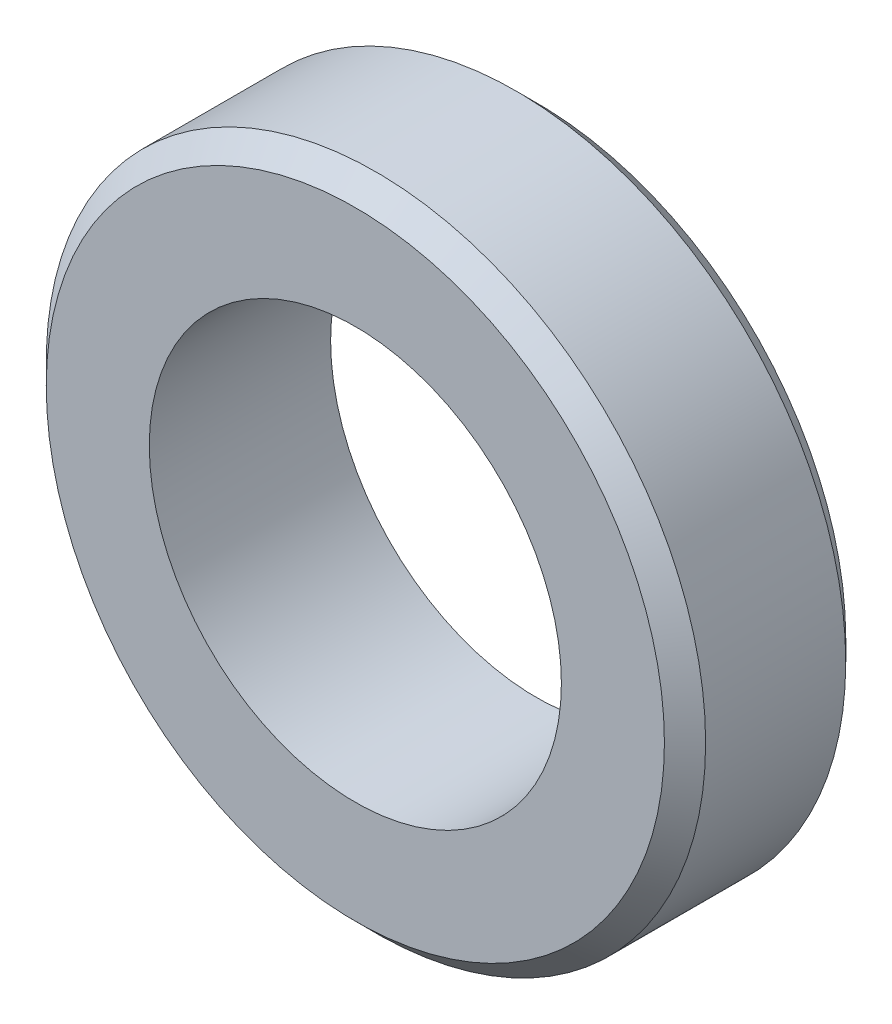
SolidWorks part; units mm, degrees
ref_plane "Front Plane" through (0, 0, 0) normal (0, 0, 1) x (1, 0, 0)
ref_plane "Top Plane" through (0, 0, 0) normal (0, 1, 0) x (1, 0, 0)
ref_plane "Right Plane" through (0, 0, 0) normal (1, 0, 0) x (0, 0, -1)
sketch "Sketch1" plane through (0, 0, 0) normal (0, 0, 1) x (1, 0, 0)
  circle A0 centre (0, 0) radius 12.7
  circle A1 centre (0, 0) radius 7.9375
  dimension "D1" = 25.4
  dimension "D2" = 15.875
extrude "Boss-Extrude1" add sketch "Sketch1" along normal blind 6.985
chamfer "Chamfer1" distance 0.7937 angle 45 2 edges at (12.7, 0, 6.985) (12.7, 0, 0)
ref_plane "Plane1" through (0, 0, 3.4925) normal (0, 0, -1) x (-1, 0, 0)
